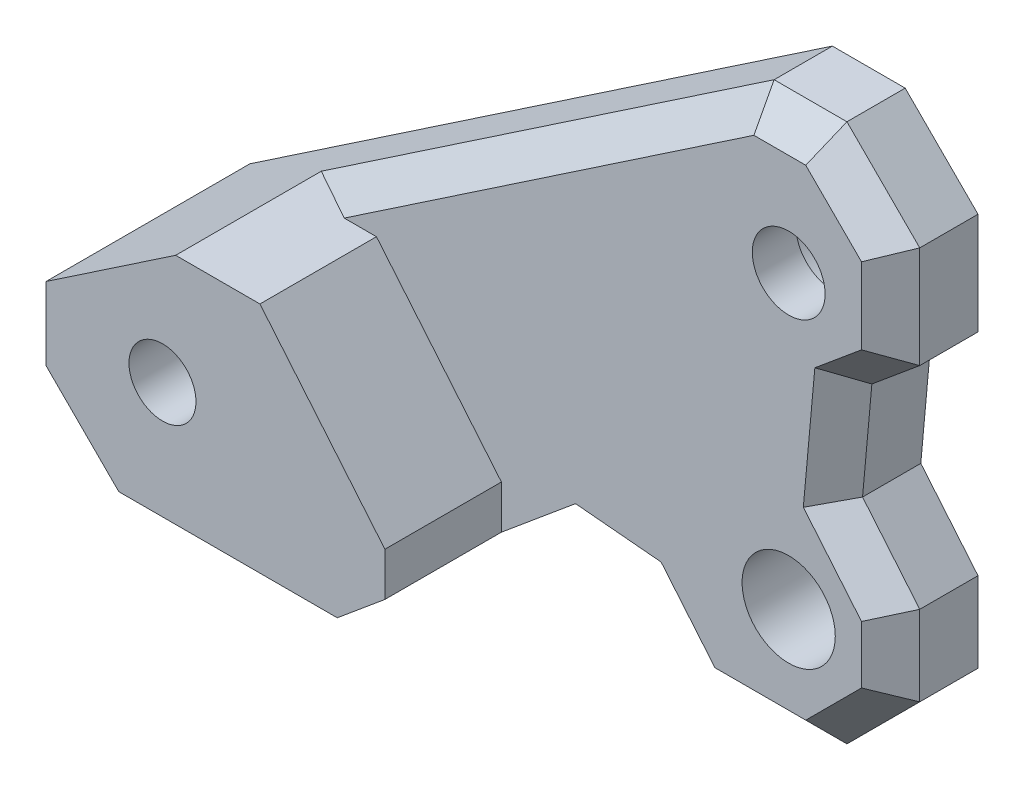
SolidWorks part; units mm, degrees
ref_plane "前视基准面" through (0, 0, 0) normal (0, 0, 1) x (1, 0, 0)
ref_plane "上视基准面" through (0, 0, 0) normal (0, 1, 0) x (1, 0, 0)
ref_plane "右视基准面" through (0, 0, 0) normal (1, 0, 0) x (0, 0, -1)
other "Configuration Table"
sketch "草图1" plane through (0, 0, 0) normal (0, 0, 1) x (1, 0, 0)
  line L0 (21.0459, 22.9739) -> (-18.9541, -4.0261)
  line L1 (-18.9541, -14.0261) -> (1.0459, -14.0261)
  line L2 (-18.9541, -14.0261) -> (-18.9541, -4.0261)
  line L3 (21.0459, 22.9739) -> (31.0459, 22.9739)
  line L4 (31.0459, -14.0261) -> (31.0459, -3.521)
  line L5 (-18.9541, -14.0261) -> (31.0459, 22.9739) construction
  line L6 (-7.7814, 3.5155) -> (31.0459, -14.0261) construction
  line L7 (31.0459, 10.9739) -> (23.9172, 5.0334)
  line L8 (23.9172, 5.0334) -> (31.0459, -3.521)
  line L9 (11.0786, -5.6654) -> (1.0459, -14.0261)
  line L10 (11.0786, -5.6654) -> (18.0459, -14.0261)
  line L11 (31.0459, 10.9739) -> (31.0459, 22.9739)
  line L12 (18.0459, -14.0261) -> (31.0459, -14.0261)
  circle A0 centre (-10.9541, -6.0261) radius 2.3
  circle A1 centre (24.0459, -6.0261) radius 3.2
  circle A2 centre (24.0459, 13.9739) radius 2.5
  point P0 (0, 0)
  dimension "D3" = 6.4
  dimension "D4" = 4.6
  dimension "D5" = 5
  dimension "D1" = 10
  dimension "D2" = 37
  dimension "D6" = 35
  dimension "D7" = 20
  dimension "D8" = 7
  dimension "D9" = 8
  dimension "D10" = 10
  dimension "D11" = 50
  dimension "D12" = 12
  dimension "D13" = 20
  dimension "D14" = 13
extrude "凸台-拉伸1" add sketch "草图1" along normal blind 6
chamfer "倒角1" distance 5 angle 45 5 edges at (31.0459, 22.9739, 3) (-18.9541, -14.0261, 3) (11.0786, -5.6654, 3) (23.9172, 5.0334, 3) (31.0459, -14.0261, 3)
sketch "草图3" plane through (0, 0, 6) normal (0, 0, 1) x (1, 0, 0)
  line L0 (-10.0504, 1.984) -> (-4.2627, 1.984)
  line L1 (-4.2627, 1.984) -> (4.3181, -8.313)
  line L2 (4.3181, -8.313) -> (4.3181, -11.2992)
  line L16 (31.0459, 10.9739) -> (31.0459, 17.9739)
  line L17 (31.0459, 17.9739) -> (26.0459, 22.9739)
  line L18 (26.0459, 22.9739) -> (21.0459, 22.9739)
  line L19 (21.0459, 22.9739) -> (-18.9541, -4.0261)
  line L20 (-18.9541, -4.0261) -> (-18.9541, -9.0261)
  line L21 (-18.9541, -9.0261) -> (-13.9541, -14.0261)
  line L22 (-13.9541, -14.0261) -> (1.0459, -14.0261)
  line L23 (1.0459, -14.0261) -> (7.2375, -8.8663)
  line L24 (7.2375, -8.8663) -> (14.2796, -9.5065)
  line L25 (14.2796, -9.5065) -> (18.0459, -14.0261)
  line L26 (18.0459, -14.0261) -> (26.0459, -14.0261)
  line L27 (26.0459, -14.0261) -> (31.0459, -9.0261)
  line L28 (31.0459, -9.0261) -> (31.0459, -3.521)
  line L29 (31.0459, -3.521) -> (27.1181, 1.1923)
  line L30 (27.1181, 1.1923) -> (27.7583, 8.2343)
  line L31 (27.7583, 8.2343) -> (31.0459, 10.9739)
  line L35 (-10.0504, 1.984) -> (-18.9541, -4.0261)
  line L36 (-18.9541, -4.0261) -> (-18.9541, -9.0261)
  line L37 (-18.9541, -9.0261) -> (-13.9541, -14.0261)
  line L38 (-13.9541, -14.0261) -> (1.0459, -14.0261)
  line L39 (1.0459, -14.0261) -> (4.3181, -11.2992)
  dimension "D1" = 0
extrude "凸台-拉伸2" add sketch "草图3" along normal blind 8
sketch "草图4" plane through (0, 0, 6) normal (0, 0, -1) x (-1, 0, 0)
  circle A1 centre (10.9541, -6.0261) radius 2.3
  circle A2 centre (10.9541, -6.0261) radius 2.3
  dimension "D1" = 0
extrude "切除-拉伸1" cut sketch "草图4" against normal blind 8
chamfer "倒角3" distance 2 angle 45 12 edges at (10.7586, -9.1864, 6) (16.1627, -11.7663, 6) (22.0459, -14.0261, 6) (28.5459, -11.5261, 6) (31.0459, -6.2736, 6) (29.082, -1.1644, 6) (27.4382, 4.7133, 6) (5.4977, 12.479, 6) (23.5459, 22.9739, 6) (28.5459, 20.4739, 6) (31.0459, 14.4739, 6) (29.4021, 9.6041, 6)
sketch "草图5" plane through (0, 0, 0) normal (0, 0, -1) x (-1, 0, 0)
  circle A0 centre (-24.0459, 13.9739) radius 4.05
  dimension "D1" = 8.1
extrude "切除-拉伸2" cut sketch "草图5" against normal blind 3
fillet "圆角1" radius 0.5 1 edges at (19.9959, 13.9739, 0)
